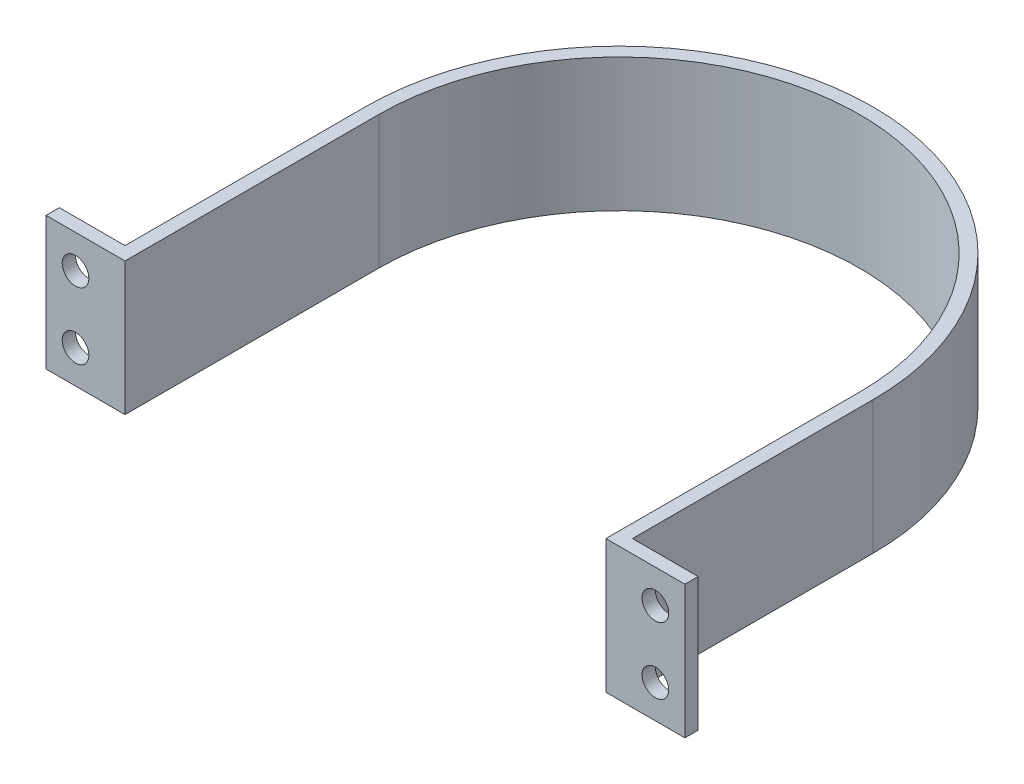
SolidWorks part; units mm, degrees
other "Markup1"
sketch "Sketch14" plane through (-178.835, 31.75, 121.05) normal (-0.0444, 0.3923, 0.9187) x (0.9976, 0.0664, 0.0198)
material "1060 Alloy"
ref_plane "Front Plane" through (0, 0, 0) normal (0, 0, 1) x (1, 0, 0)
ref_plane "Top Plane" through (0, 0, 0) normal (0, 1, 0) x (1, 0, 0)
ref_plane "Right Plane" through (0, 0, 0) normal (1, 0, 0) x (0, 0, -1)
sketch "Sketch1" plane through (0, 0, 0) normal (0, 1, 0) x (1, 0, 0)
  line L0 (0, 0) -> (-121.05, 0) construction
  line L1 (0, 0) -> (0, -121.05) construction
  line L2 (0, -121.05) -> (-152.4, -121.05)
  line L3 (-114.7, 0) -> (-114.7, -121.05)
  line L4 (-121.05, 0) -> (-121.05, -121.05)
  line L5 (0, -114.7) -> (-152.4, -114.7)
  line L6 (-152.4, -114.7) -> (-152.4, -121.05)
  line L7 (-120.3819, -12.7) -> (-121.05, -12.7)
  line L8 (152.4, -114.7) -> (152.4, -121.05)
  line L9 (0, -114.7) -> (152.4, -114.7)
  line L10 (-113.9947, -12.7) -> (-114.7, -12.7)
  line L11 (121.05, 0) -> (121.05, -121.05)
  line L12 (114.7, 0) -> (114.7, -121.05)
  line L13 (0, -121.05) -> (152.4, -121.05)
  circle A0 centre (0, 0) radius 102
  circle A1 centre (0, 0) radius 114.7
  arc A3 (-114.7, -38.6912) -> (-121.05, 0) centre (0, 0) ccw
  arc A4 (-114.7, -38.6912) -> (119.5416, -19.05) centre (0, 0) ccw
  arc A5 (120.3819, -12.7) -> (120.3819, 12.7) centre (0, 0) ccw
  circle A6 centre (0, 0) radius 121.05 construction
  point P8 (-152.4, -117.875)
  point P29 (0, 0)
  dimension "D1" = 204
  dimension "D2" = 12.7
  dimension "D4" = 152.4
  dimension "D3" = 6.35
  dimension "D5" = 6.35
extrude "Boss-Extrude1" add sketch "Sketch1" along normal mid plane 63.5
sketch "Sketch15" plane through (0, 0, 121.05) normal (0, 0, 1) x (1, 0, 0)
  line L0 (-149.225, 0) -> (-127.4, 0) construction
  line L5 (-127.4, 31.75) -> (-127.4, -31.75)
  line L6 (-127.4, 31.75) -> (-127.4, -31.75)
  line L7 (-138.3125, 0) -> (-138.3125, 31.75) construction
  line L8 (-149.225, 31.75) -> (-149.225, -31.75)
  line L9 (-149.225, 31.75) -> (-149.225, -31.75)
  line L10 (-114.7, 31.75) -> (-152.4, 31.75) construction
  line L12 (0, 0) -> (0, 31.75) construction
  line L13 (114.7, 31.75) -> (-114.7, 31.75) construction
  circle A6 centre (-138.3125, 15.875) radius 6.35
  circle A7 centre (-138.3125, -15.875) radius 6.35
  circle A8 centre (138.3125, -15.875) radius 6.35
  circle A9 centre (138.3125, 15.875) radius 6.35
  dimension "D1" = 12.7
  dimension "D2" = 3.175
extrude "Cut-Extrude1" cut sketch "Sketch15" against normal through all contours A6 | A7 | A8 | A9
